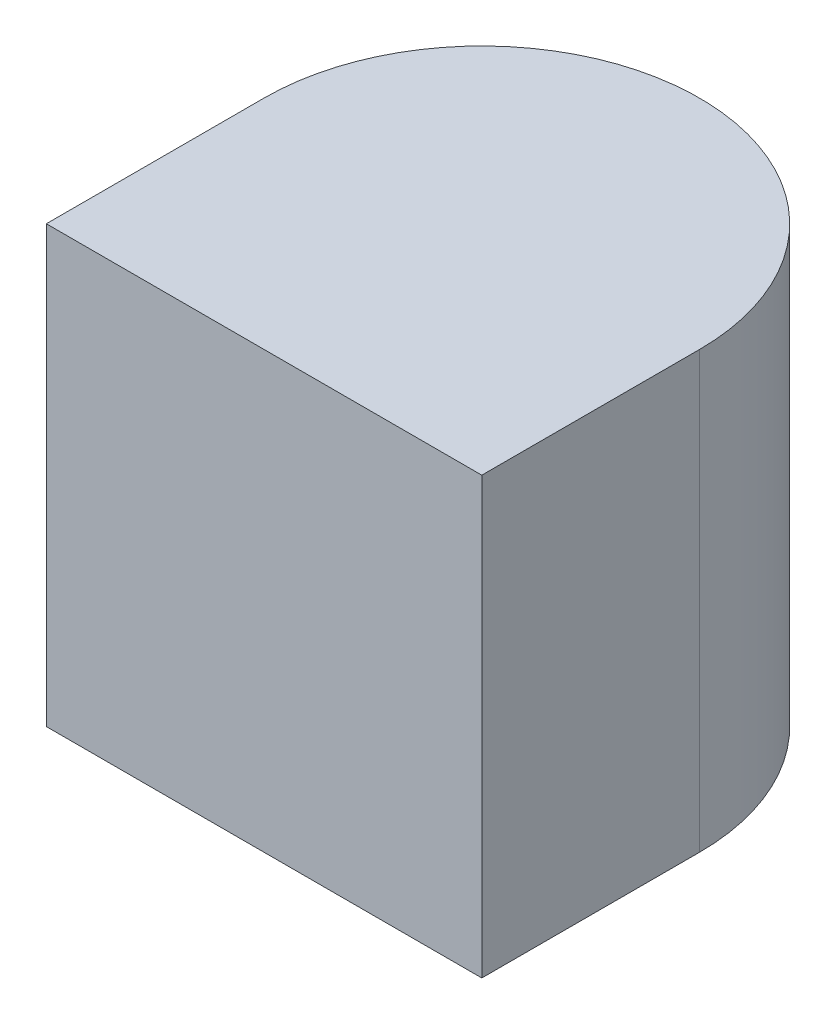
SolidWorks part; units mm, degrees
ref_plane "Přední rovina" through (0, 0, 0) normal (0, 0, 1) x (1, 0, 0)
ref_plane "Horní rovina" through (0, 0, 0) normal (0, 1, 0) x (1, 0, 0)
ref_plane "Pravá rovina" through (0, 0, 0) normal (1, 0, 0) x (0, 0, -1)
sketch "Sketch1" plane through (0, 0, 0) normal (0, 1, 0) x (1, 0, 0)
  line L1 (-10, -20) -> (10, -20)
  line L2 (-10, -20) -> (-10, -10)
  line L4 (10, -20) -> (10, -10)
  arc A0 (-10, -10) -> (10, -10) centre (0, -10) cw
  dimension "D1" = 20
  dimension "D2" = 10
extrude "Boss-Extrude1" add sketch "Sketch1" along normal blind 20
equation "\"R\" = 10'Radius"
equation "\"D1@Sketch1\"=\"R\"*2"
equation "\"D2@Sketch1\"=\"R\""
equation "\"H\"= 20'Extrude height"
equation "\"D1@Boss-Extrude1\"=\"H\""
